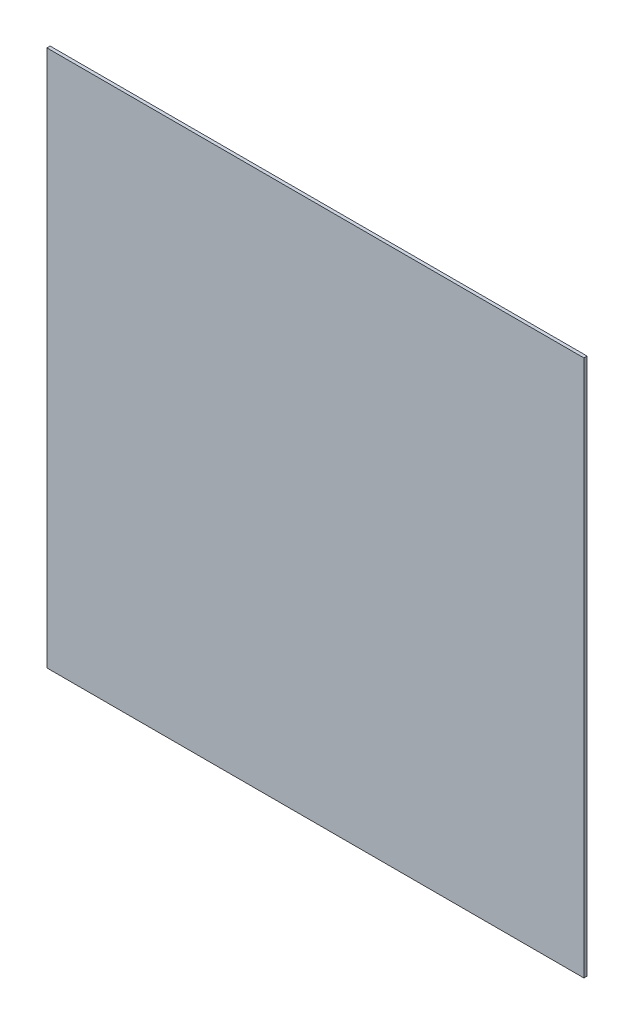
SolidWorks part; units mm, degrees
ref_plane "前视基准面" through (0, 0, 0) normal (0, 0, 1) x (1, 0, 0)
ref_plane "上视基准面" through (0, 0, 0) normal (0, 1, 0) x (1, 0, 0)
ref_plane "右视基准面" through (0, 0, 0) normal (1, 0, 0) x (0, 0, -1)
other "Configuration Table"
sketch "草图1" plane through (0, 0, 0) normal (0, 0, 1) x (1, 0, 0)
  line L1 (-250, 250) -> (250, 250)
  line L2 (-250, 250) -> (-250, -250)
  line L3 (-250, -250) -> (250, -250)
  line L4 (250, 250) -> (250, -250)
  line L5 (-250, 250) -> (250, -250) construction
  line L6 (-250, -250) -> (250, 250) construction
  point P0 (0, 0)
  point P5 (686.849, -250)
  dimension "D1" = 500
  dimension "D2" = 500
extrude "凸台-拉伸1" add sketch "草图1" along normal blind 3
